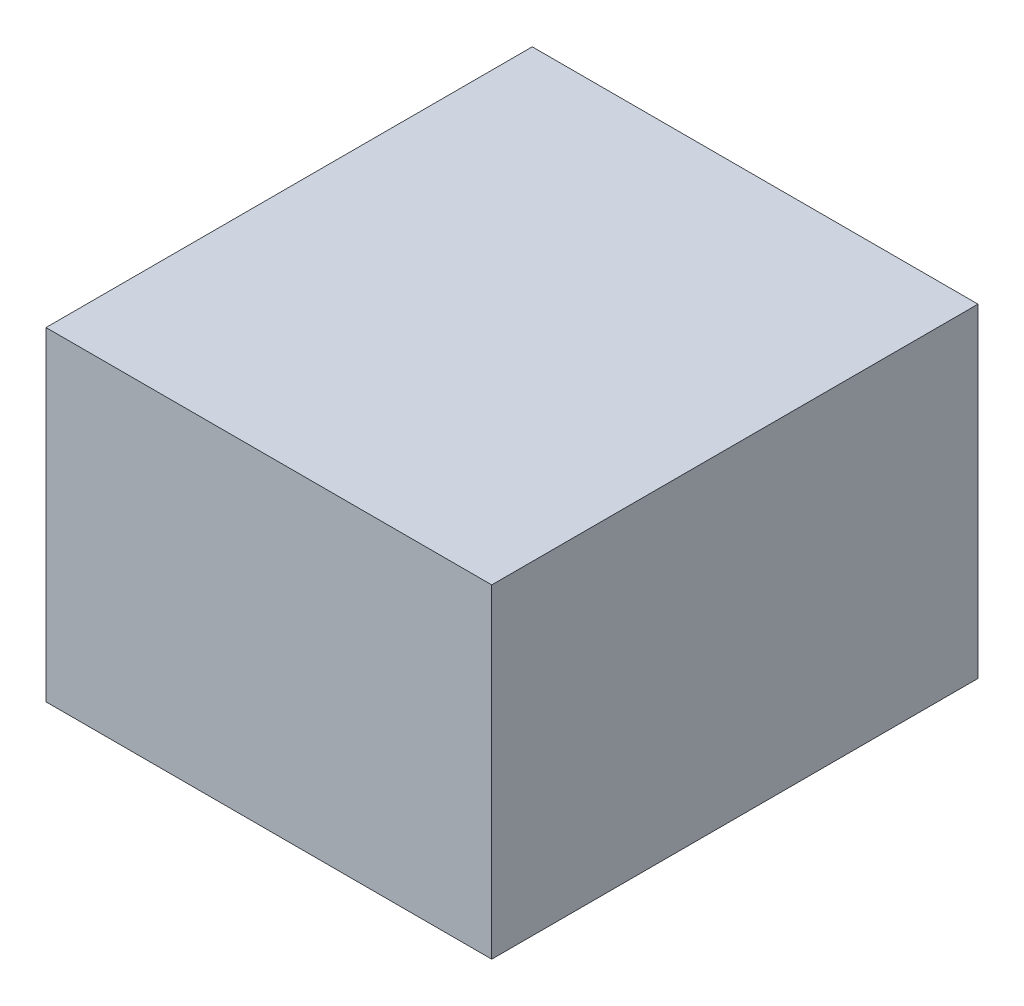
SolidWorks part; units mm, degrees
ref_plane "Front Plane" through (0, 0, 0) normal (0, 0, 1) x (1, 0, 0)
ref_plane "Top Plane" through (0, 0, 0) normal (0, 1, 0) x (1, 0, 0)
ref_plane "Right Plane" through (0, 0, 0) normal (1, 0, 0) x (0, 0, -1)
sketch "Sketch1" plane through (0, 0, 0) normal (0, 1, 0) x (1, 0, 0)
  line L1 (-45.72, 36.576) -> (24.13, 36.576)
  line L2 (-45.72, 36.576) -> (-45.72, -39.624)
  line L3 (-45.72, -39.624) -> (24.13, -39.624)
  line L4 (24.13, 36.576) -> (24.13, -39.624)
  dimension "D1" = 76.2
  dimension "D2" = 69.85
extrude "Boss-Extrude1" add sketch "Sketch1" along normal blind 50.8
